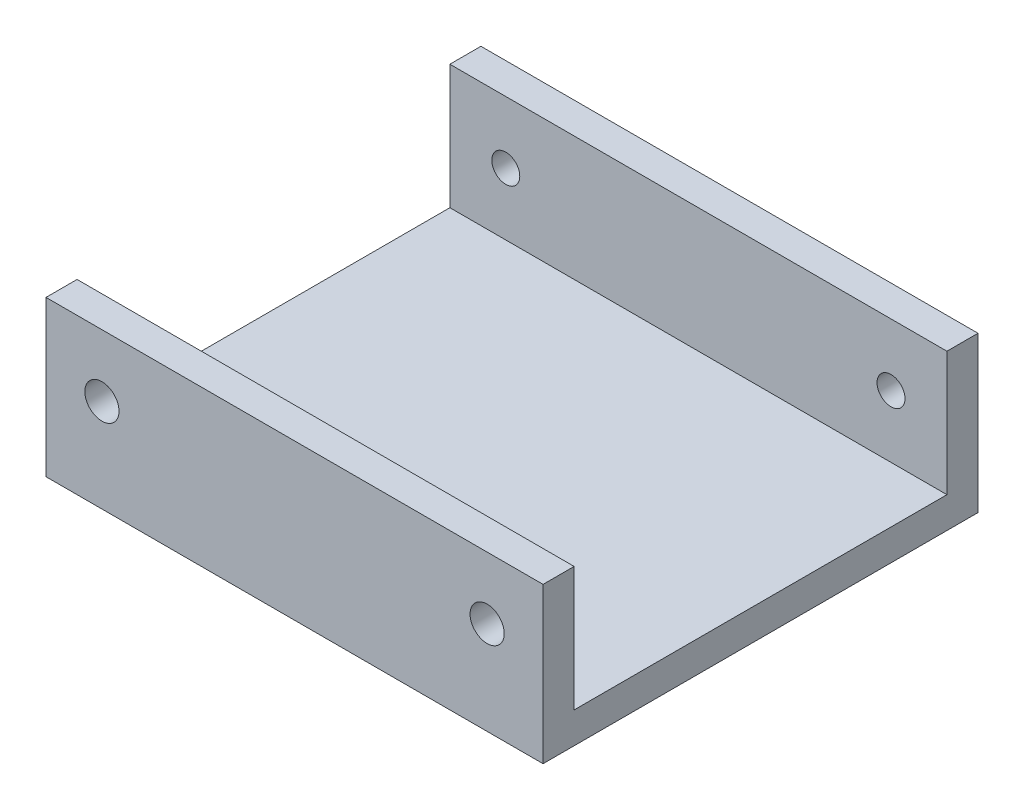
SolidWorks part; units mm, degrees
ref_plane "Front Plane" through (0, 0, 0) normal (0, 0, 1) x (1, 0, 0)
ref_plane "Top Plane" through (0, 0, 0) normal (0, 1, 0) x (1, 0, 0)
ref_plane "Right Plane" through (0, 0, 0) normal (1, 0, 0) x (0, 0, -1)
sketch "Sketch1" plane through (0, 0, 0) normal (0, 0, 1) x (1, 0, 0)
  line L0 (40, 20) -> (40, 0) construction
  line L1 (0, 0) -> (80, 0)
  line L2 (0, 0) -> (0, 20)
  line L3 (0, 20) -> (80, 20)
  line L4 (80, 0) -> (80, 20)
  line L5 (0, 10) -> (80, 10) construction
  circle A0 centre (9, 10) radius 2.25
  circle A1 centre (71, 10) radius 2.25
  dimension "D3" = 4.5
  dimension "D4" = 62
  dimension "D1" = 20
  dimension "D2" = 80
extrude "Boss-Extrude1" add sketch "Sketch1" along normal blind 5
sketch "Sketch2" plane through (0, 0, 0) normal (0, -1, 0) x (1, 0, 0)
  line L0 (80, 5) -> (80, 0) construction
  line L1 (0, 0) -> (80, 0)
  line L2 (0, 0) -> (0, 70)
  line L3 (0, 70) -> (80, 70)
  line L4 (80, 0) -> (80, 70)
  dimension "D1" = 70
extrude "Boss-Extrude2" add sketch "Sketch2" along normal blind 5
sketch "Sketch3" plane through (0, 0, 70) normal (0, 0, 1) x (1, 0, 0)
  line L0 (80, -5) -> (80, 0) construction
  line L1 (0, 0) -> (80, 0)
  line L2 (0, 0) -> (0, 20)
  line L3 (0, 20) -> (80, 20)
  line L4 (80, 0) -> (80, 20)
  line L5 (40, 20) -> (40, 0) construction
  line L6 (0, 10) -> (80, 10) construction
  circle A0 centre (9, 10) radius 2.75
  circle A1 centre (71, 10) radius 2.75
  dimension "D2" = 5.5
  dimension "D1" = 20
  dimension "D3" = 62
extrude "Boss-Extrude3" add sketch "Sketch3" against normal blind 5
